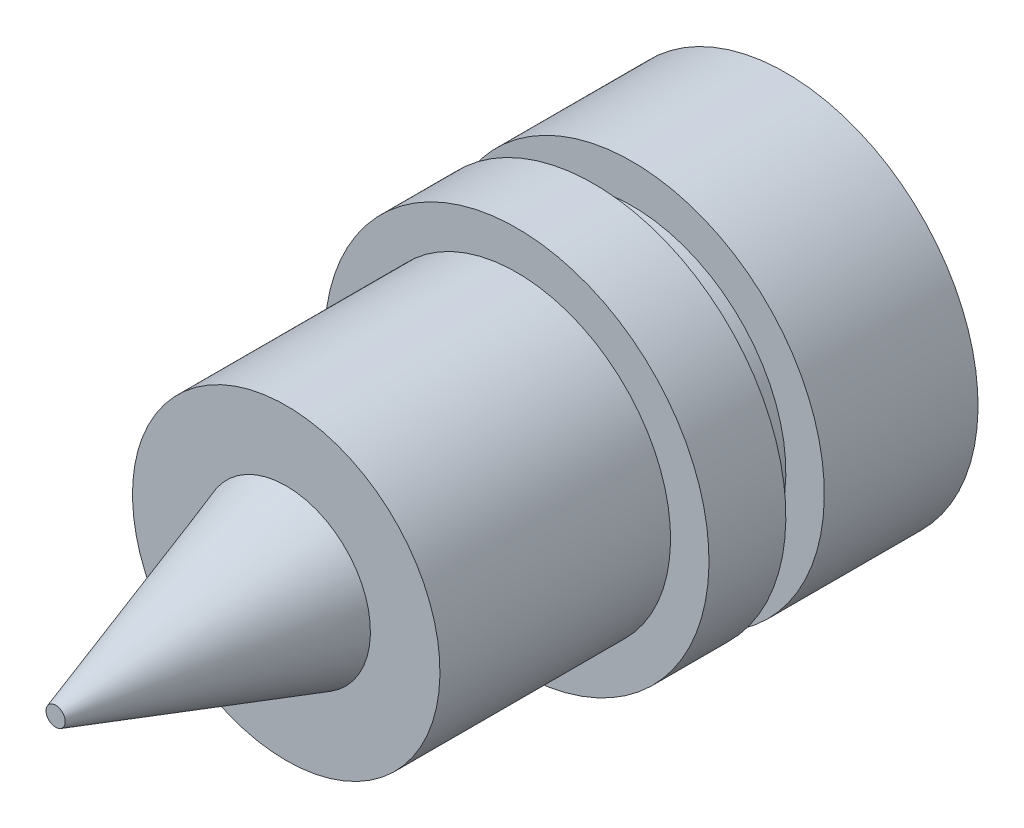
SolidWorks part; units mm, degrees
ref_plane "Alzado" through (0, 0, 0) normal (0, 0, 1) x (1, 0, 0)
ref_plane "Planta" through (0, 0, 0) normal (0, 1, 0) x (1, 0, 0)
ref_plane "Vista lateral" through (0, 0, 0) normal (1, 0, 0) x (0, 0, -1)
sketch "Croquis3" plane through (0, 0, 0) normal (1, 0, 0) x (0, 0, -1)
  line L0 (0, 0) -> (0, 2.5)
  line L1 (0, 2.5) -> (-2, 2.5)
  line L2 (-3.5, 2.5) -> (-3.5, 2)
  line L3 (-3.5, 2) -> (-6.5, 2)
  line L5 (-9.5, 0) -> (0, 0)
  line L6 (-2.5, 2.5) -> (-2.5, 2)
  line L7 (-2.5, 2) -> (-2, 2)
  line L8 (-2, 2) -> (-2, 2.5)
  line L9 (-2.5, 2.5) -> (-3.5, 2.5)
  line L12 (-6.5, 2) -> (-6.5, 1.0955)
  line L13 (-6.5, 1.0955) -> (-9.5, 0.125)
  line L14 (-9.5, 0.125) -> (-9.5, 0)
  dimension "D1" = 2.5
  dimension "D2" = 2
  dimension "D3" = 0.5
  dimension "D4" = 1
  dimension "D5" = 2
  dimension "D6" = 0.5
  dimension "D7" = 3
  dimension "D8" = 0.125
  dimension "D9" = 3
revolve "Revolución1" add sketch "Croquis3" angle 360 about L5
sketch "Croquis4" plane through (0, 0, 0) normal (0, 0, -1) x (-1, 0, 0)
  line L1 (1.75, -0.5) -> (-1.75, -0.5)
  line L2 (1.75, -0.5) -> (1.75, 0.5)
  line L3 (1.75, 0.5) -> (-1.75, 0.5)
  line L4 (-1.75, -0.5) -> (-1.75, 0.5)
  line L5 (1.75, -0.5) -> (-1.75, 0.5) construction
  line L6 (1.75, 0.5) -> (-1.75, -0.5) construction
  point P0 (0, 0)
  dimension "D1" = 1
  dimension "D2" = 3.5
extrude "Cortar-Extruir1" cut sketch "Croquis4" against normal blind 1
